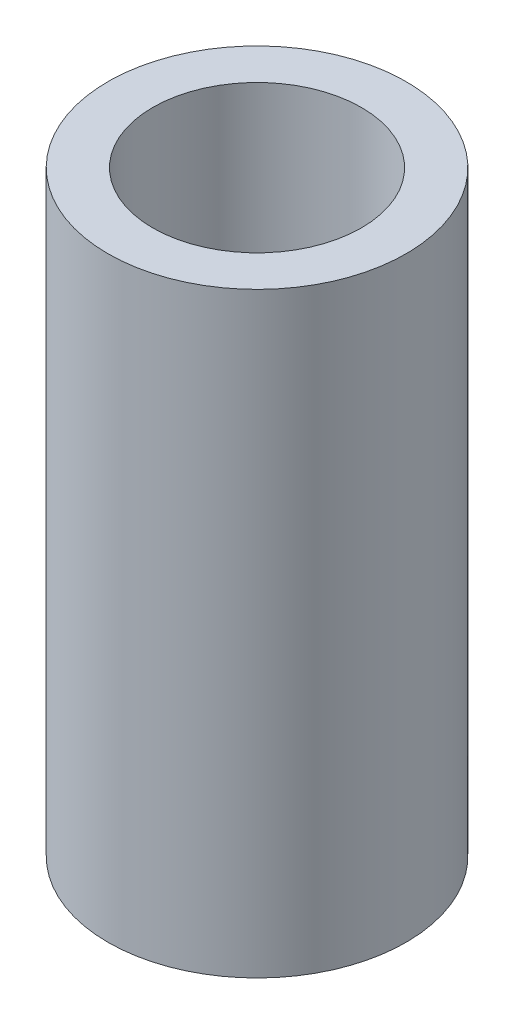
SolidWorks part; units mm, degrees
material "ABS"
ref_plane "Front Plane" through (0, 0, 0) normal (0, 0, 1) x (1, 0, 0)
ref_plane "Top Plane" through (0, 0, 0) normal (0, 1, 0) x (1, 0, 0)
ref_plane "Right Plane" through (0, 0, 0) normal (1, 0, 0) x (0, 0, -1)
sketch "Sketch1" plane through (0, 0, 0) normal (0, 1, 0) x (1, 0, 0)
  circle A0 centre (0, 0) radius 2.5
  circle A1 centre (0, 0) radius 1.75
  dimension "D1" = 5
  dimension "D2" = 3.5
extrude "Boss-Extrude1" add sketch "Sketch1" along normal blind 10
